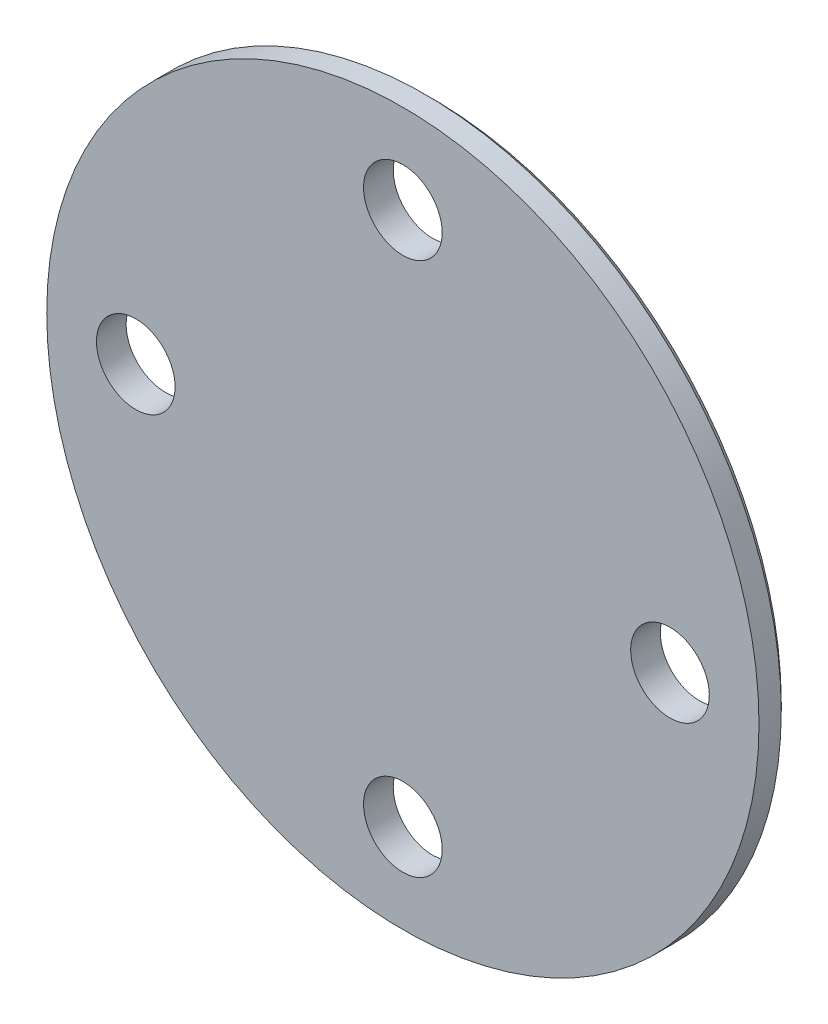
SolidWorks part; units mm, degrees
ref_plane "Front Plane" through (0, 0, 0) normal (0, 0, 1) x (1, 0, 0)
ref_plane "Top Plane" through (0, 0, 0) normal (0, 1, 0) x (1, 0, 0)
ref_plane "Right Plane" through (0, 0, 0) normal (1, 0, 0) x (0, 0, -1)
sketch "Sketch1" plane through (0, 0, 0) normal (0, 0, 1) x (1, 0, 0)
  circle A0 centre (0, 0) radius 24
  dimension "D1" = 48
extrude "Extrude1" add sketch "Sketch1" along normal blind 2
hole_wizard "M5 Clearance Hole1" positions "Sketch3" profile "Sketch2" hole size "M5" standard "Ansi Metric" end condition through all
sketch "Sketch3" plane through (0, 0, 2) normal (0, 0, 1) x (1, 0, 0)
  point P0 (0, 18)
  dimension "D1" = 18
sketch "Sketch2" plane through (0, 18, 2) normal (1, 0, 0) x (0, -1, 0)
  line L0 (0, 0) -> (0, 2)
  line L1 (0, 2) -> (2.65, 2)
  line L2 (2.65, 2) -> (2.65, 0)
  line L5 (2.65, 0) -> (0, 0)
  line L11 (0, -6.35) -> (0, 107.95) construction
  dimension "Thru Hole Dia." = 5.3
  dimension "Thru Hole Depth" = 2
pattern_circular "CirPattern1" count 4 over 360 about axis through (0, 0, 0) along (0, 0, 1) of "M5 Clearance Hole1"
chamfer "Chamfer1" distance 0.5 angle 45 1 edges at (24, 0, 0)
sketch "Sketch5" plane through (0, 0, 0) normal (0, 0, -1) x (-1, 0, 0)
  circle A0 centre (0, 0) radius 11 construction
  text T0 "MECH 2630"
  dimension "D1" = 22
extrude "Extrude3" add sketch "Sketch5" along normal blind 0.6
